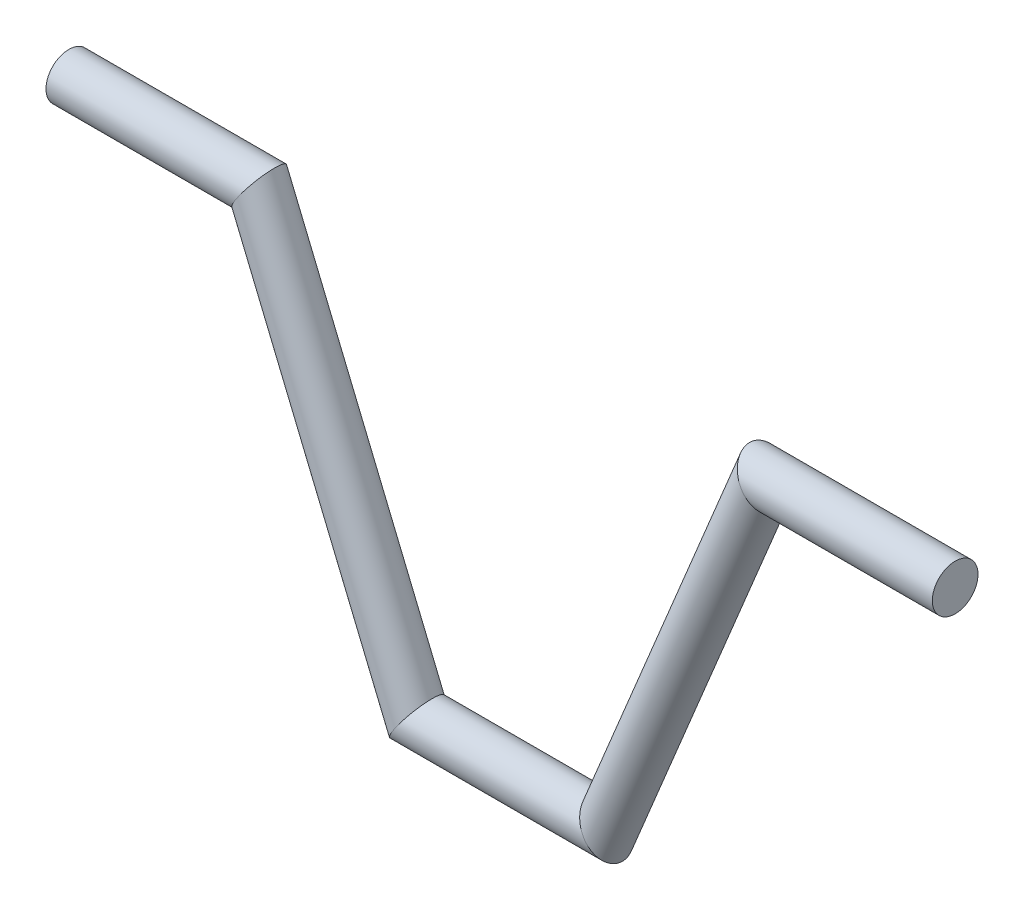
SolidWorks part; units mm, degrees
material "ASTM A36 Steel"
ref_plane "Front Plane" through (0, 0, 0) normal (0, 0, 1) x (1, 0, 0)
ref_plane "Top Plane" through (0, 0, 0) normal (0, 1, 0) x (1, 0, 0)
ref_plane "Right Plane" through (0, 0, 0) normal (1, 0, 0) x (0, 0, -1)
sketch "Sketch1" plane through (0, 0, 0) normal (0, 0, 1) x (1, 0, 0)
  line L0 (-58.2107, 50) -> (-33.2107, 50)
  line L1 (-33.2107, 50) -> (-12.5, 0)
  line L2 (-12.5, 0) -> (12.5, 0)
  line L3 (12.5, 0) -> (33.2107, 50)
  line L4 (33.2107, 50) -> (58.2107, 50)
  line L5 (0, 0) -> (0, 43.1692) construction
  dimension "D1" = 25
  dimension "D2" = 25
  dimension "D3" = 45
  dimension "D4" = 22.5
  dimension "D5" = 50
ref_plane "Plane1" through (49, 0, 0) normal (1, 0, 0) x (0, 0, -1)
sketch "Sketch2" plane through (49, 0, 0) normal (1, 0, 0) x (0, 0, -1)
  circle A0 centre (0, 50) radius 3
  dimension "D1" = 6
sweep "Sweep3" add profiles "Sketch2" path "Sketch1"
